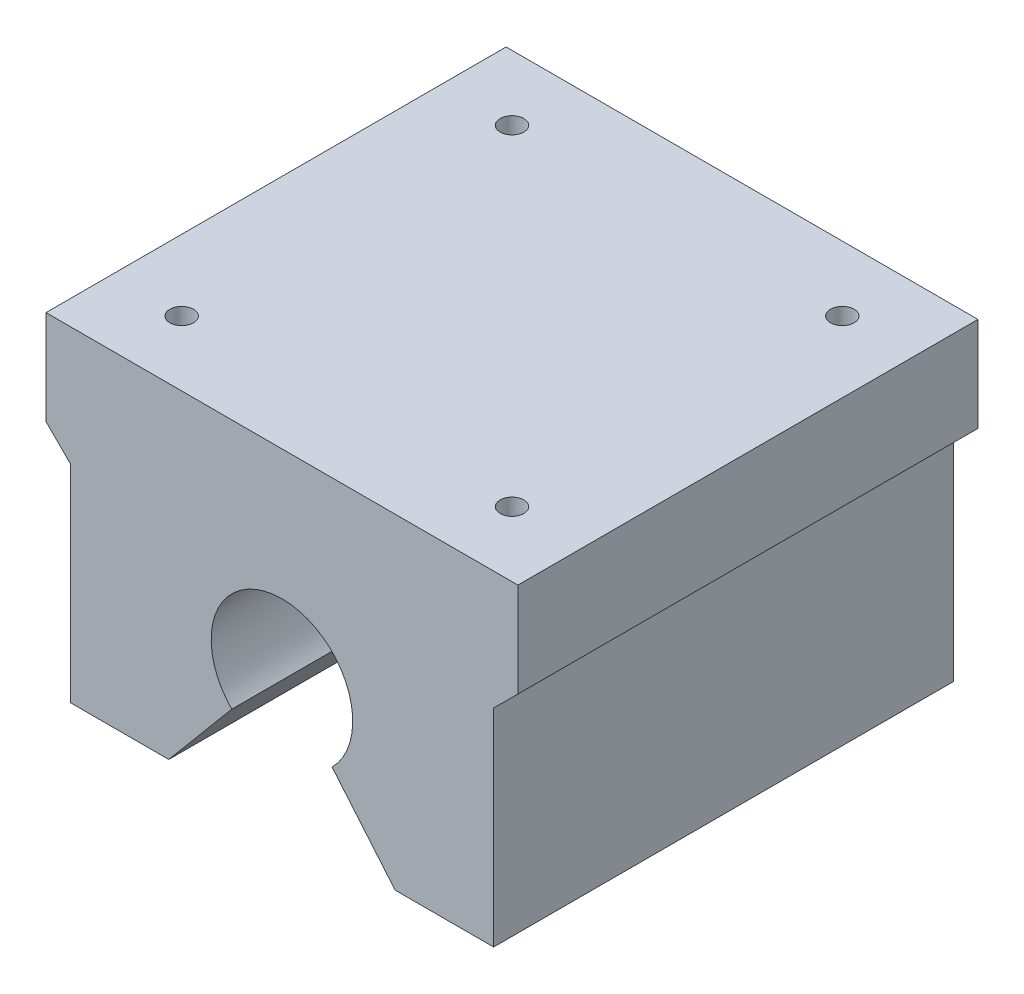
SolidWorks part; units mm, degrees
ref_plane "Front Plane" through (0, 0, 0) normal (0, 0, 1) x (1, 0, 0)
ref_plane "Top Plane" through (0, 0, 0) normal (0, 1, 0) x (1, 0, 0)
ref_plane "Right Plane" through (0, 0, 0) normal (1, 0, 0) x (0, 0, -1)
sketch "Sketch1" plane through (0, 0, 0) normal (0, 0, 1) x (1, 0, 0)
  line L0 (0, 0) -> (0, 38.5119) construction
  line L1 (-4.25, -4.2353) -> (38.3645, -4.2353) construction
  line L2 (20, 17) -> (-20, 17)
  line L3 (-20, 17) -> (-20, 9)
  line L4 (-20, 9) -> (-17.9435, 6.9435)
  line L5 (-17.9435, 6.9435) -> (-17.9435, -10.6)
  line L6 (-17.9435, -10.6) -> (-9.5906, -10.6)
  line L7 (-9.5906, -10.6) -> (-4.25, -4.2353)
  line L8 (9.5906, -10.6) -> (4.25, -4.2353)
  line L9 (17.9435, -10.6) -> (9.5906, -10.6)
  line L10 (17.9435, 6.9435) -> (17.9435, -10.6)
  line L11 (20, 9) -> (17.9435, 6.9435)
  line L12 (20, 17) -> (20, 9)
  arc A0 (-4.25, -4.2353) -> (4.25, -4.2353) centre (0, 0) cw
  point P19 (0, 17)
  dimension "D1" = 20
  dimension "D3" = 6
  dimension "D2" = 4.25
  dimension "D4" = 8
  dimension "D5" = 27.6
  dimension "D6" = 80
  dimension "D7" = 17
extrude "Boss-Extrude1" add sketch "Sketch1" along normal blind 39
sketch "Sketch2" plane through (0, 17, 0) normal (0, 1, 0) x (1, 0, 0)
  line L1 (0, 1.1084) -> (0, -6.1266) construction
  line L2 (-20, -19.5) -> (-15.4499, -19.5) construction
  circle A0 centre (-14, -33.5) radius 1
  circle A1 centre (14, -33.5) radius 1
  circle A2 centre (-14, -5.5) radius 1
  circle A3 centre (14, -5.5) radius 1
  dimension "D1" = 14
  dimension "D2" = 14
  dimension "D4" = 14
  dimension "D5" = 14
  dimension "D6" = 14
  dimension "D7" = 14
  dimension "D8" = 2
  dimension "D9" = 2
  dimension "D10" = 2
  dimension "D11" = 2
  dimension "D3" = 14
extrude "Cut-Extrude1" cut sketch "Sketch2" against normal blind 10
